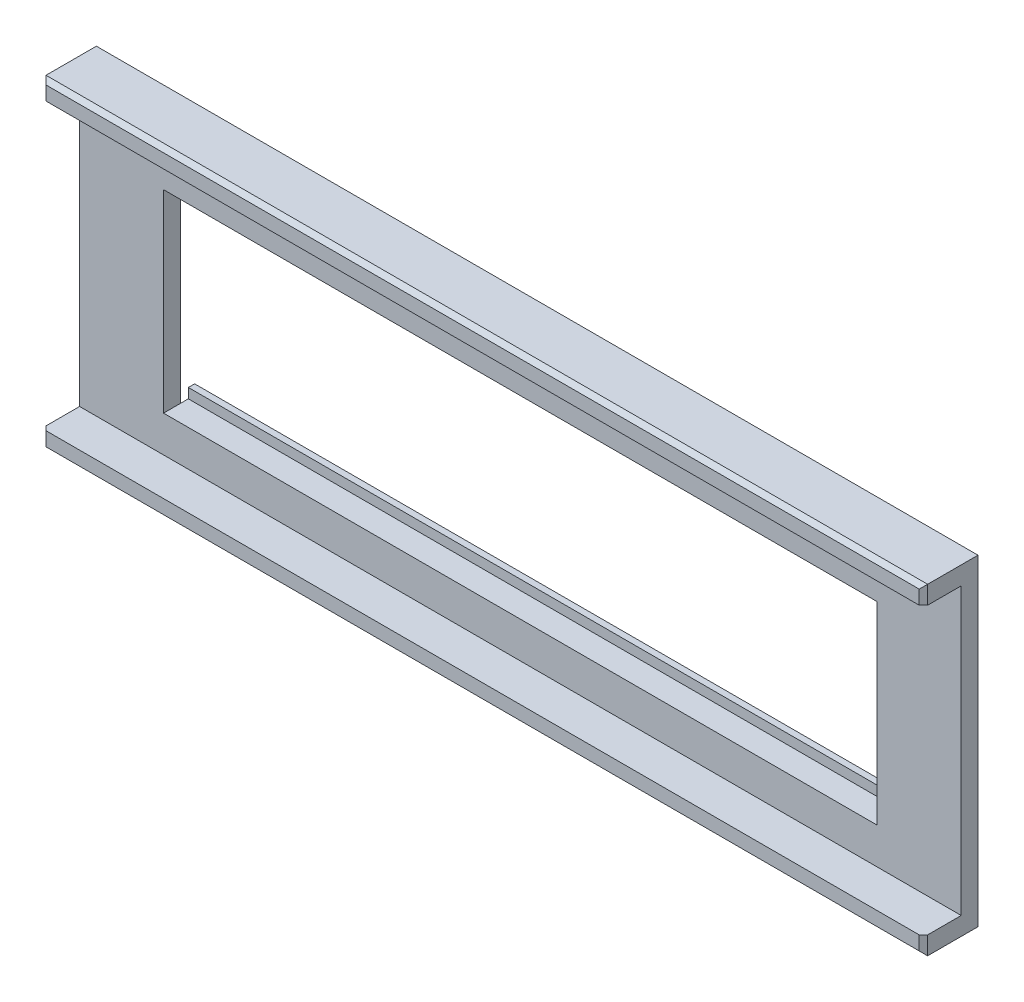
SolidWorks part; units mm, degrees
material "自定义塑料"
ref_plane "Front" through (0, 0, 0) normal (0, 0, 1) x (1, 0, 0)
ref_plane "Top" through (0, 0, 0) normal (0, 1, 0) x (1, 0, 0)
ref_plane "Right" through (0, 0, 0) normal (1, 0, 0) x (0, 0, -1)
sketch "草图1" plane through (0, 0, 0) normal (0, 0, 1) x (1, 0, 0)
  line L0 (-105, 38.325) -> (105, -38.325) construction
  line L5 (-105, -38.325) -> (105, -38.325)
  line L6 (-105, -38.325) -> (-105, 38.325)
  line L7 (-105, 38.325) -> (105, 38.325)
  line L8 (105, -38.325) -> (105, 38.325)
  line L9 (-105, -38.325) -> (105, 38.325) construction
  line L11 (-85, 20.725) -> (85, 20.725)
  line L12 (-85, 20.725) -> (-85, -25.375)
  line L13 (-85, -25.375) -> (85, -25.375)
  line L14 (85, 20.725) -> (85, -25.375)
  point P8 (0, 0)
  dimension "D1" = 210
  dimension "D2" = 76.65
  dimension "D3" = 20
  dimension "D4" = 20
  dimension "D5" = 17.6
  dimension "D6" = 12.95
extrude "凸台-拉伸1" add sketch "草图1" along normal blind 13
sketch "草图2" plane through (0, 0, 13) normal (0, 0, 1) x (1, 0, 0)
  line L0 (-105, -38.325) -> (105, -38.325) construction
  line L1 (-105, 34) -> (105, 34)
  line L3 (-105, -34) -> (105, -34)
  line L6 (-105, 38.325) -> (-105, -38.325) construction
  line L8 (105, -34) -> (105, 34)
  line L9 (-105, -34) -> (-105, 34)
  line L10 (105, -38.325) -> (105, 38.325) construction
  dimension "D1" = 4.325
  dimension "D3" = 68
extrude "切除-拉伸1" cut sketch "草图2" against normal blind 9
chamfer "倒角1" distance 1 angle 45 6 edges at (-105, -36.1625, 13) (-105, 36.1625, 13) (0, -38.325, 13) (105, -36.1625, 13) (105, 36.1625, 13) (0, 38.325, 13)
hole_wizard "打孔尺寸(%根据十字)槽半沉头木螺钉的类型1" positions "草图4" profile "草图5" countersink size "M5" standard "GB"
sketch "草图4" plane through (0, 0, 4) normal (0, 0, 1) x (1, 0, 0)
  line L0 (-105, -38.325) -> (-105, 38.325) construction
  line L1 (105, 38.325) -> (105, -38.325) construction
  point P0 (-95, 0)
  point P6 (95, 0)
  dimension "D1" = 10
  dimension "D2" = 10
sketch "草图5" plane through (-95, 0, 4) normal (1, 0, 0) x (0, -1, 0)
  line L0 (0, 0) -> (0, 4)
  line L1 (0, 4) -> (2.75, 4)
  line L2 (2.75, 4) -> (2.75, 2.85)
  line L3 (2.75, 2.85) -> (5.6, 0)
  line L5 (5.6, 0) -> (0, 0)
  line L6 (-2.75, 2.85) -> (-5.6, 0) construction
  line L11 (0, -6.35) -> (0, 107.95) construction
  dimension "通孔孔直径" = 5.5
  dimension "通孔孔深度" = 4
  dimension "近端锥形沉头孔直径" = 11.2
  dimension "近端锥形沉头孔角度" = 90
sketch "草图6" plane through (105, 0, 0) normal (1, 0, 0) x (0, 0, -1)
  line L0 (-12, -38.325) -> (0, -38.325) construction
  line L5 (0, 20.725) -> (0, 26.625)
  line L6 (0, -38.325) -> (0, 38.325) construction
  line L7 (0, 26.625) -> (1.9, 26.625)
  line L8 (1.9, 26.625) -> (1.9, 28.975)
  line L9 (1.9, 28.975) -> (3.4, 28.975)
  line L10 (3.4, 28.975) -> (4.9, 27.475)
  line L12 (4.9, 27.475) -> (4.9, 19.875)
  line L13 (4.9, 19.875) -> (3.4, 18.375)
  line L14 (3.4, 18.375) -> (1.9, 18.375)
  line L15 (1.9, 18.375) -> (1.9, 20.725)
  line L16 (1.9, 20.725) -> (0, 20.725)
  line L27 (-12, 38.325) -> (0, 38.325) construction
  line L28 (0, -31.275) -> (0, -25.375)
  line L29 (0, -25.375) -> (1.9, -25.375)
  line L30 (1.9, -25.375) -> (1.9, -23.025)
  line L31 (1.9, -23.025) -> (3.4, -23.025)
  line L32 (3.4, -23.025) -> (4.9, -24.525)
  line L33 (4.9, -24.525) -> (4.9, -32.125)
  line L34 (4.9, -32.125) -> (3.4, -33.625)
  line L35 (3.4, -33.625) -> (1.9, -33.625)
  line L36 (1.9, -33.625) -> (1.9, -31.275)
  line L37 (1.9, -31.275) -> (0, -31.275)
  dimension "D1" = 5.9
  dimension "D2" = 1.9
  dimension "D3" = 2.35
  dimension "D4" = 2.35
  dimension "D5" = 3
  dimension "D6" = 135
  dimension "D7" = 135
  dimension "D8" = 11.7
  dimension "D9" = 1.5
  dimension "D10" = 5.9
  dimension "D11" = 1.9
  dimension "D12" = 2.35
  dimension "D13" = 2.35
  dimension "D14" = 3
  dimension "D15" = 135
  dimension "D16" = 135
  dimension "D17" = 1.5
  dimension "D18" = 7.05
extrude "凸台-拉伸2" add sketch "草图6" against normal blind 210
sketch "草图7" plane through (0, 0, -4.9) normal (0, 0, -1) x (-1, 0, 0)
  line L1 (-105, 38.325) -> (-85, 38.325)
  line L2 (-105, 38.325) -> (-105, -38.325)
  line L3 (-105, -38.325) -> (-85, -38.325)
  line L4 (-85, 38.325) -> (-85, -38.325)
  line L5 (105, 38.325) -> (85, 38.325)
  line L6 (105, 38.325) -> (105, -38.325)
  line L7 (105, -38.325) -> (85, -38.325)
  line L8 (85, 38.325) -> (85, -38.325)
  dimension "D1" = 20
  dimension "D2" = 20
extrude "切除-拉伸2" cut sketch "草图7" against normal blind 4.9
